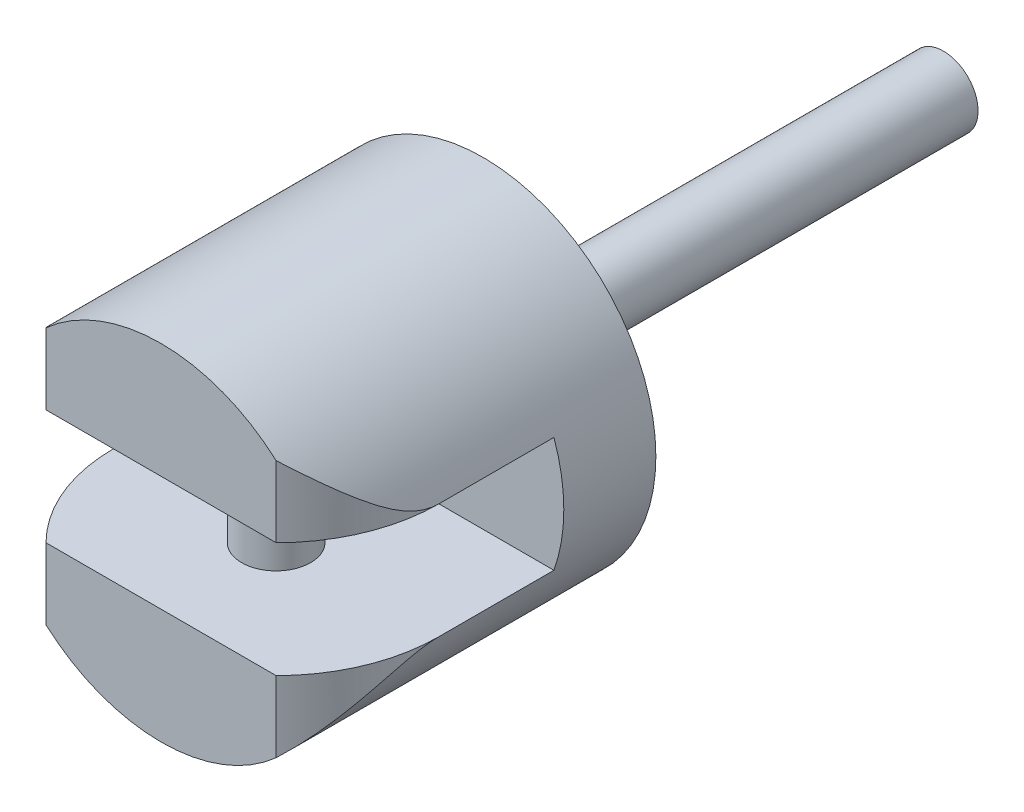
SolidWorks part; units mm, degrees
ref_plane "Front Plane" through (0, 0, 0) normal (0, 0, 1) x (1, 0, 0)
ref_plane "Top Plane" through (0, 0, 0) normal (0, 1, 0) x (1, 0, 0)
ref_plane "Right Plane" through (0, 0, 0) normal (1, 0, 0) x (0, 0, -1)
sketch "Sketch2" plane through (0, 0, 0) normal (0, 0, 1) x (1, 0, 0)
  circle A0 centre (0, 0) radius 75
  dimension "D1" = 150
extrude "Boss-Extrude1" add sketch "Sketch2" along normal blind 40
sketch "Sketch3" plane through (0, 0, 0) normal (0, 0, -1) x (-1, 0, 0)
  circle A0 centre (0, 0) radius 15
  dimension "D1" = 30
extrude "Boss-Extrude2" add sketch "Sketch3" along normal blind 200
sketch "Sketch4" plane through (0, 0, 40) normal (0, 0, 1) x (1, 0, 0)
  line L1 (-70.7107, 25) -> (70.7107, 25)
  line L2 (70.7107, -25) -> (-70.7107, -25)
  line L3 (0, 0) -> (0, -25) construction
  circle A0 centre (0, 0) radius 75 construction
  arc A1 (-70.7107, -25) -> (70.7107, -25) centre (0, 0) ccw
  arc A3 (-70.7107, 25) -> (-70.7107, -25) centre (0, 0) ccw construction
  arc A4 (70.7107, 25) -> (-70.7107, 25) centre (0, 0) ccw
  arc A5 (70.7107, -25) -> (70.7107, 25) centre (0, 0) ccw construction
  dimension "D1" = 25
extrude "Boss-Extrude3" add sketch "Sketch4" along normal blind 100
ref_plane "Plane2" through (0, 0, 90) normal (0, 0, 1) x (1, 0, 0)
sketch "Sketch13" plane through (0, 0, 90) normal (0, 0, 1) x (1, 0, 0)
  line L0 (0, 25) -> (0, -25)
  line L1 (-70.7107, 25) -> (70.7107, 25) construction
  line L2 (70.7107, -25) -> (-70.7107, -25) construction
sweep "Sweep2" add path "Sketch13" circular profile diameter 30 parameters "D3"=30
sketch "Sketch20" plane through (0, 0, 0) normal (0, 1, 0) x (1, 0, 0)
  line L0 (-70.7107, -40) -> (-70.7107, -140) construction
  line L1 (-70.7107, -90) -> (70.7107, -90) construction
  line L2 (70.7107, -140) -> (70.7107, -40) construction
  line L3 (70.7107, -90) -> (70.7107, -188.2911)
  line L4 (70.7107, -188.2911) -> (-70.7107, -188.2911)
  line L5 (-70.7107, -188.2911) -> (-70.7107, -90)
  arc A0 (-70.7107, -90) -> (70.7107, -90) centre (0, -90) ccw
  arc A1 (70.7107, -90) -> (-70.7107, -90) centre (0, -90) ccw construction
  point P9 (70.7107, -188.2911)
extrude "Cut-Extrude1" cut sketch "Sketch20" against normal through all both and the other way through all contours L5 A0 L3 L4
